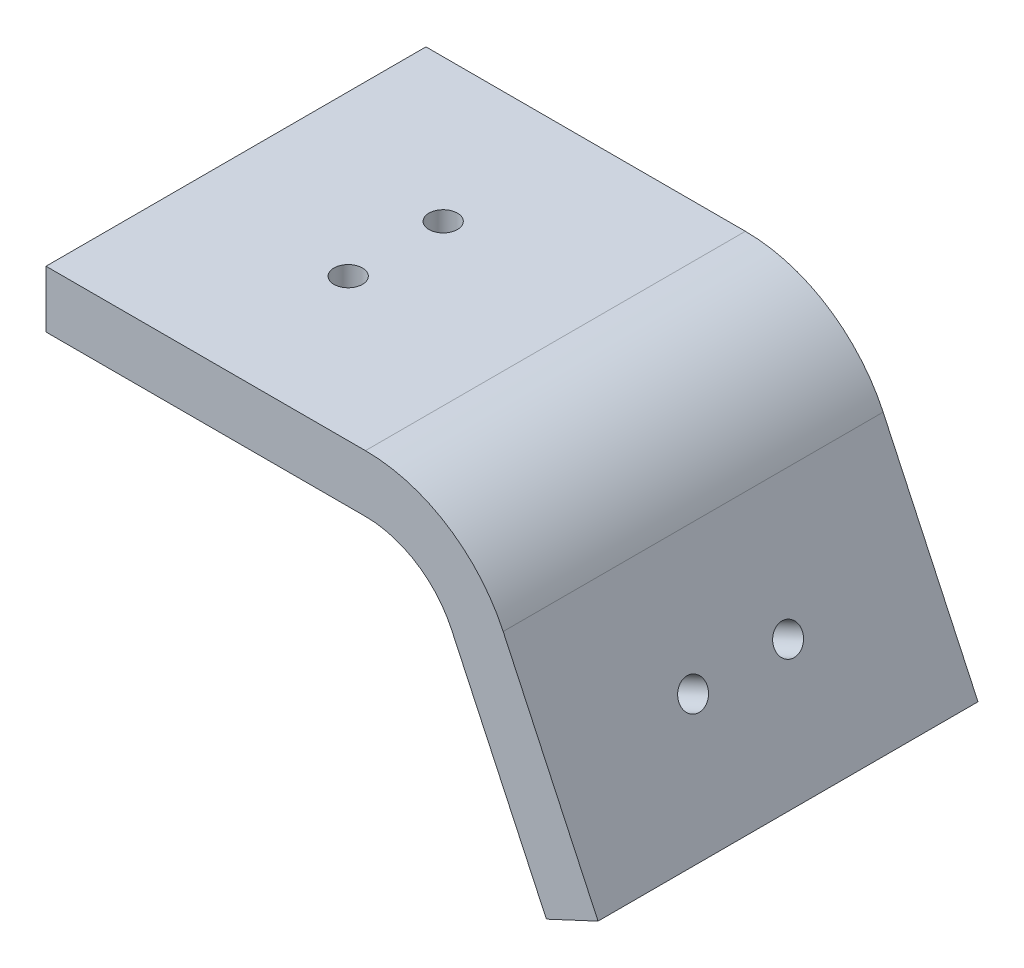
SolidWorks part; units mm, degrees
material "Acrilico TEC"
ref_plane "Front Plane" through (0, 0, 0) normal (0, 0, 1) x (1, 0, 0)
ref_plane "Top Plane" through (0, 0, 0) normal (0, 1, 0) x (1, 0, 0)
ref_plane "Right Plane" through (0, 0, 0) normal (1, 0, 0) x (0, 0, -1)
sketch "Sketch1" plane through (0, 0, 0) normal (0, 0, 1) x (1, 0, 0)
  line L0 (0, 0) -> (-9.9862, 21.4154)
  line L1 (-19.0493, 27.1892) -> (-52.6785, 27.1892)
  line L2 (5.4378, 2.5357) -> (-4.5483, 23.9511)
  line L3 (-19.0493, 33.1892) -> (-52.6785, 33.1892)
  line L4 (-52.6785, 33.1892) -> (-52.6785, 27.1892)
  line L5 (5.4378, 2.5357) -> (0, 0)
  arc A0 (-9.9862, 21.4154) -> (-19.0493, 27.1892) centre (-19.0493, 17.1892) ccw
  arc A1 (-4.5483, 23.9511) -> (-19.0493, 33.1892) centre (-19.0493, 17.1892) ccw
  point P6 (-12.6785, 27.1892)
  dimension "D4" = 10
  dimension "D1" = 115
  dimension "D2" = 30
  dimension "D3" = 40
  dimension "D5" = 6
extrude "Boss-Extrude1" add sketch "Sketch1" along normal blind 40
sketch "Sketch2" plane through (0, 33.1892, 0) normal (0, 1, 0) x (1, 0, 0)
  line L0 (-19.0493, -20) -> (-52.6785, -20) construction
  line L1 (-19.0493, -40) -> (-19.0493, 0) construction
  line L2 (-52.6785, -40) -> (-52.6785, 0) construction
  line L3 (-35.8639, -15) -> (-35.8639, -20)
  circle A0 centre (-35.8639, -15) radius 1.5
  circle A1 centre (-35.8639, -25) radius 1.5
  dimension "D2" = 3
  dimension "D1" = 5
extrude "Cut-Extrude1" cut sketch "Sketch2" against normal blind 40
sketch "Sketch3" plane through (5.4378, 2.5357, 0) normal (0.9063, 0.4226, 0) x (0, 0, -1)
  line L0 (-20, 23.6293) -> (-20, 0) construction
  line L1 (-40, 23.6293) -> (0, 23.6293) construction
  line L2 (-40, 0) -> (0, 0) construction
  line L3 (-15, 11.8146) -> (-20, 11.8146) construction
  circle A0 centre (-15, 11.8146) radius 1.5
  circle A1 centre (-25, 11.8146) radius 1.5
  dimension "D2" = 3
  dimension "D1" = 5
extrude "Cut-Extrude2" cut sketch "Sketch3" against normal blind 40
